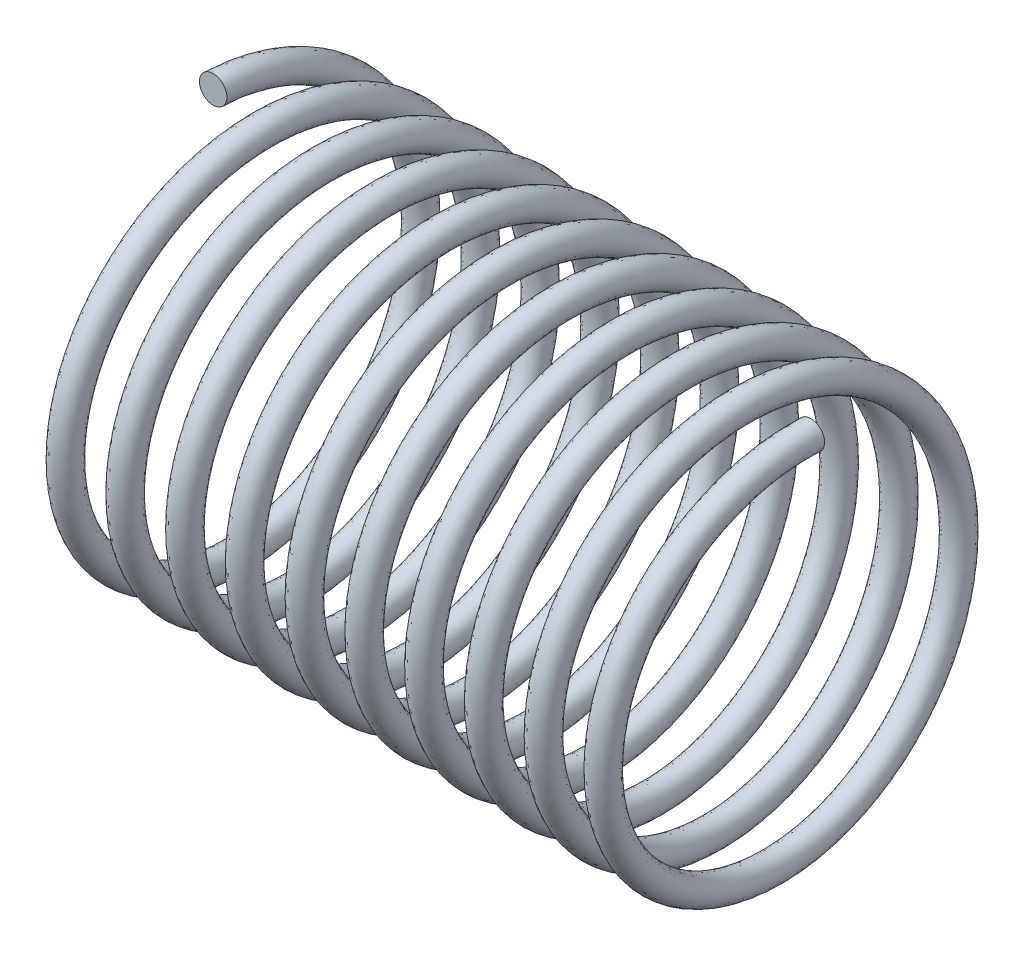
SolidWorks part; units mm, degrees
material "Alloy Steel"
ref_plane "Front Plane" through (0, 0, 0) normal (0, 0, 1) x (1, 0, 0)
ref_plane "Top Plane" through (0, 0, 0) normal (0, 1, 0) x (1, 0, 0)
ref_plane "Right Plane" through (0, 0, 0) normal (1, 0, 0) x (0, 0, -1)
sketch "Sketch1" plane through (0, 0, 0) normal (1, 0, 0) x (0, 0, -1)
  circle A0 centre (0, 0) radius 5.6
  dimension "D1" = 11.2
curve "Helix/Spiral1" pitch 1.74 height 17.4 turns 10
sketch "Sketch2" plane through (0, 0, 0) normal (0, 0, 1) x (1, 0, 0)
  circle A0 centre (0, 5.6) radius 0.4
  spline S0 degree 3 poles (0, 5.6) (0.036, 5.6) (0.1089, 5.3084) (0.2175, 4.0629) (0.3263, 2.1988) (0.435, 0) (0.5438, -2.1988) (0.6525, -4.0629) (0.7613, -5.3084) (0.87, -5.7458) (0.9788, -5.3084) (1.0875, -4.0629) (1.1963, -2.1988) (1.305, 0) (1.4138, 2.1988) (1.5225, 4.0629) (1.6313, 5.3084) (1.74, 5.7458) (1.8488, 5.3084) (1.9575, 4.0629) (2.0663, 2.1988) (2.175, 0) (2.2837, -2.1988) (2.3925, -4.0629) (2.5012, -5.3084) (2.61, -5.7458) (2.7187, -5.3084) (2.8275, -4.0629) (2.9362, -2.1988) (3.045, 0) (3.1537, 2.1988) (3.2625, 4.0629) (3.3712, 5.3084) (3.48, 5.7458) (3.5887, 5.3084) (3.6975, 4.0629) (3.8062, 2.1988) (3.915, 0) (4.0237, -2.1988) (4.1325, -4.0629) (4.2412, -5.3084) (4.35, -5.7458) (4.4588, -5.3084) (4.5675, -4.0629) (4.6762, -2.1988) (4.785, 0) (4.8937, 2.1988) (5.0025, 4.0629) (5.1113, 5.3084) (5.22, 5.7458) (5.3288, 5.3084) (5.4375, 4.0629) (5.5463, 2.1988) (5.655, 0) (5.7638, -2.1988) (5.8725, -4.0629) (5.9813, -5.3084) (6.09, -5.7458) (6.1988, -5.3084) (6.3075, -4.0629) (6.4163, -2.1988) (6.525, 0) (6.6338, 2.1988) (6.7425, 4.0629) (6.8513, 5.3084) (6.96, 5.7458) (7.0688, 5.3084) (7.1775, 4.0629) (7.2863, 2.1988) (7.395, 0) (7.5038, -2.1988) (7.6125, -4.0629) (7.7213, -5.3084) (7.83, -5.7458) (7.9388, -5.3084) (8.0475, -4.0629) (8.1563, -2.1988) (8.265, 0) (8.3738, 2.1988) (8.4825, 4.0629) (8.5913, 5.3084) (8.7, 5.7458) (8.8088, 5.3084) (8.9175, 4.0629) (9.0263, 2.1988) (9.135, 0) (9.2438, -2.1988) (9.3525, -4.0629) (9.4613, -5.3084) (9.57, -5.7458) (9.6788, -5.3084) (9.7875, -4.0629) (9.8963, -2.1988) (10.005, 0) (10.1137, 2.1988) (10.2225, 4.0629) (10.3312, 5.3084) (10.44, 5.7458) (10.5487, 5.3084) (10.6575, 4.0629) (10.7662, 2.1988) (10.875, 0) (10.9837, -2.1988) (11.0925, -4.0629) (11.2012, -5.3084) (11.31, -5.7458) (11.4187, -5.3084) (11.5275, -4.0629) (11.6362, -2.1988) (11.745, 0) (11.8537, 2.1988) (11.9625, 4.0629) (12.0712, 5.3084) (12.18, 5.7458) (12.2887, 5.3084) (12.3975, 4.0629) (12.5062, 2.1988) (12.615, 0) (12.7237, -2.1988) (12.8325, -4.0629) (12.9412, -5.3084) (13.05, -5.7458) (13.1587, -5.3084) (13.2675, -4.0629) (13.3762, -2.1988) (13.485, 0) (13.5937, 2.1988) (13.7025, 4.0629) (13.8112, 5.3084) (13.92, 5.7458) (14.0287, 5.3084) (14.1375, 4.0629) (14.2462, 2.1988) (14.355, 0) (14.4637, -2.1988) (14.5725, -4.0629) (14.6812, -5.3084) (14.79, -5.7458) (14.8987, -5.3084) (15.0075, -4.0629) (15.1162, -2.1988) (15.225, 0) (15.3337, 2.1988) (15.4425, 4.0629) (15.5512, 5.3084) (15.66, 5.7458) (15.7687, 5.3084) (15.8775, 4.0629) (15.9862, 2.1988) (16.095, 0) (16.2037, -2.1988) (16.3125, -4.0629) (16.4212, -5.3084) (16.53, -5.7458) (16.6387, -5.3084) (16.7475, -4.0629) (16.8562, -2.1988) (16.965, 0) (17.0737, 2.1988) (17.1825, 4.0629) (17.2911, 5.3084) (17.364, 5.6) (17.4, 5.6) knots 0 0 0 0 0.00625 0.0125 0.01875 0.025 0.03125 0.0375 0.04375 0.05 0.05625 0.0625 0.06875 0.075 0.08125 0.0875 0.09375 0.1 0.10625 0.1125 0.11875 0.125 0.13125 0.1375 0.14375 0.15 0.15625 0.1625 0.16875 0.175 0.18125 0.1875 0.19375 0.2 0.20625 0.2125 0.21875 0.225 0.23125 0.2375 0.24375 0.25 0.25625 0.2625 0.26875 0.275 0.28125 0.2875 0.29375 0.3 0.30625 0.3125 0.31875 0.325 0.33125 0.3375 0.34375 0.35 0.35625 0.3625 0.36875 0.375 0.38125 0.3875 0.39375 0.4 0.40625 0.4125 0.41875 0.425 0.43125 0.4375 0.44375 0.45 0.45625 0.4625 0.46875 0.475 0.48125 0.4875 0.49375 0.5 0.50625 0.5125 0.51875 0.525 0.53125 0.5375 0.54375 0.55 0.55625 0.5625 0.56875 0.575 0.58125 0.5875 0.59375 0.6 0.60625 0.6125 0.61875 0.625 0.63125 0.6375 0.64375 0.65 0.65625 0.6625 0.66875 0.675 0.68125 0.6875 0.69375 0.7 0.70625 0.7125 0.71875 0.725 0.73125 0.7375 0.74375 0.75 0.75625 0.7625 0.76875 0.775 0.78125 0.7875 0.79375 0.8 0.80625 0.8125 0.81875 0.825 0.83125 0.8375 0.84375 0.85 0.85625 0.8625 0.86875 0.875 0.88125 0.8875 0.89375 0.9 0.90625 0.9125 0.91875 0.925 0.93125 0.9375 0.94375 0.95 0.95625 0.9625 0.96875 0.975 0.98125 0.9875 0.99375 1 1 1 1 construction
  dimension "D2" = 0.8
  dimension "D1" = 5.6
sweep "Sweep1" add profiles "Sketch2" path "Helix/Spiral1"
sketch "Sketch3" plane through (0, 0, 0) normal (1, 0, 0) x (0, 0, -1)
  circle A0 centre (0, 0) radius 6
  dimension "D1" = 12
